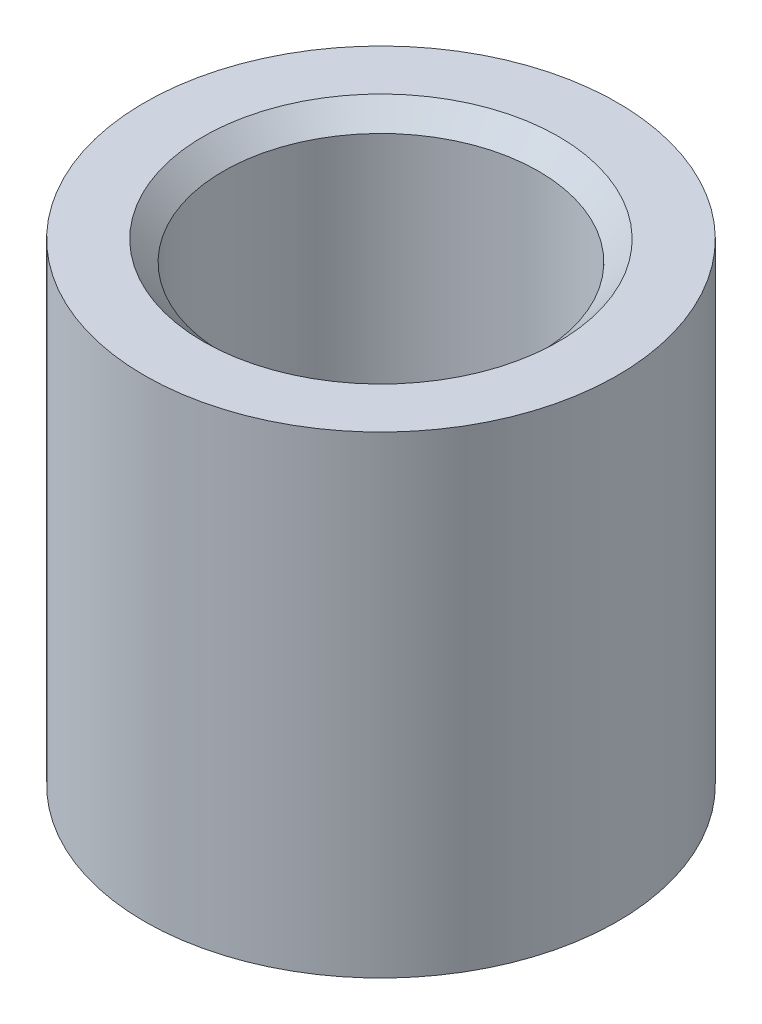
SolidWorks part; units mm, degrees
ref_plane "Front Plane" through (0, 0, 0) normal (0, 0, 1) x (1, 0, 0)
ref_plane "Top Plane" through (0, 0, 0) normal (0, 1, 0) x (1, 0, 0)
ref_plane "Right Plane" through (0, 0, 0) normal (1, 0, 0) x (0, 0, -1)
sketch "Sketch1" plane through (0, 0, 0) normal (0, 1, 0) x (1, 0, 0)
  circle A0 centre (0, 0) radius 3
  circle A1 centre (0, 0) radius 2
  dimension "D1" = 6
  dimension "D2" = 1
extrude "Boss-Extrude1" add sketch "Sketch1" along normal blind 6
sketch "Sketch3" plane through (0, 6, 0) normal (0, 1, 0) x (1, 0, 0)
  circle A0 centre (0, 0) radius 2 construction
  circle A1 centre (0, 0) radius 2.254
  circle A3 centre (0, 0) radius 2
  dimension "D1" = 0.254
extrude "Cut-Extrude1" cut sketch "Sketch3" against normal blind 0.254 draft 45 contours A1
ref_plane "Plane1" through (0, 3, 0) normal (0, 1, 0) x (1, 0, 0)
mirror "Mirror1" about plane through (0, 3, 0) normal (0, 1, 0) of "Cut-Extrude1"
